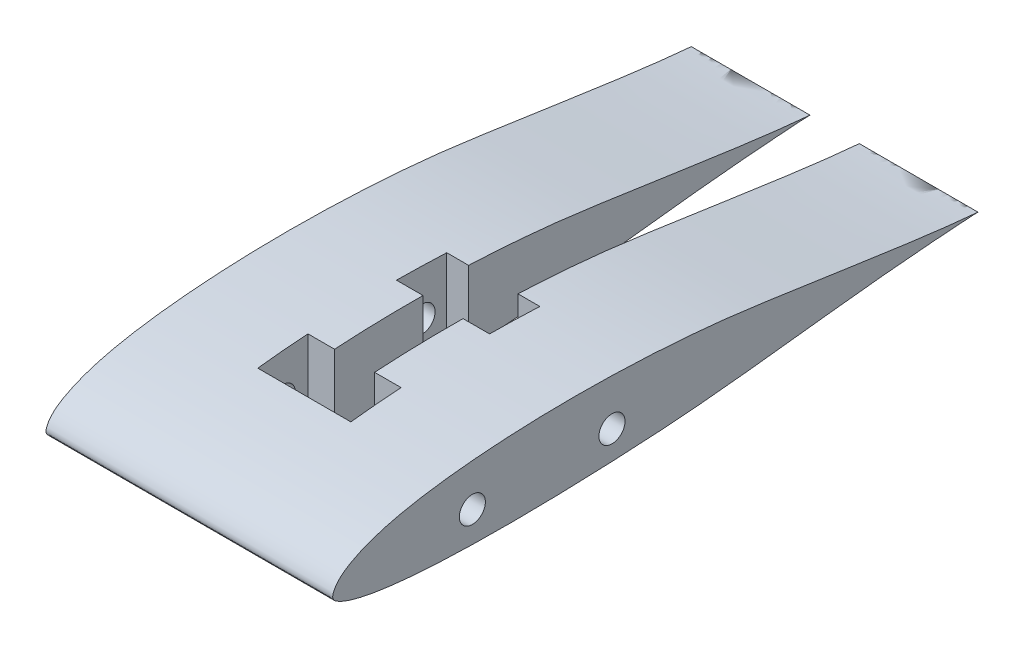
SolidWorks part; units mm, degrees
material "blue foam"
ref_plane "Front Plane" through (0, 0, 0) normal (0, 0, 1) x (1, 0, 0)
ref_plane "Top Plane" through (0, 0, 0) normal (0, 1, 0) x (1, 0, 0)
ref_plane "Right Plane" through (0, 0, 0) normal (1, 0, 0) x (0, 0, -1)
curve "Curve1"
  spline degree 3 poles (0, 0.9957, 0.0001) (0, 1.0011, -0.0001) (0, 0.9959, 0.0003) (0, 0.9917, 0.0009) (0, 0.9816, 0.0019) (0, 0.9692, 0.0034) (0, 0.953, 0.0054) (0, 0.9339, 0.008) (0, 0.9119, 0.0111) (0, 0.8872, 0.0148) (0, 0.8601, 0.019) (0, 0.8309, 0.0237) (0, 0.7998, 0.0287) (0, 0.7672, 0.0341) (0, 0.7332, 0.0396) (0, 0.6982, 0.0453) (0, 0.6625, 0.0509) (0, 0.6263, 0.0563) (0, 0.5898, 0.061) (0, 0.5529, 0.0649) (0, 0.5159, 0.0683) (0, 0.4788, 0.0709) (0, 0.4418, 0.0729) (0, 0.4052, 0.0743) (0, 0.3691, 0.0751) (0, 0.3338, 0.0752) (0, 0.2993, 0.0747) (0, 0.266, 0.0736) (0, 0.234, 0.072) (0, 0.2036, 0.0697) (0, 0.1748, 0.0669) (0, 0.1479, 0.0636) (0, 0.123, 0.0598) (0, 0.1002, 0.0554) (0, 0.0797, 0.0505) (0, 0.0614, 0.045) (0, 0.0455, 0.0391) (0, 0.0319, 0.0328) (0, 0.0207, 0.0264) (0, 0.0119, 0.0198) (0, 0.0055, 0.0129) (0, 0.0017, 0.0063) (0, -0.0006, 0) (0, 0.0012, -0.0062) (0, 0.0072, -0.0105) (0, 0.0154, -0.0148) (0, 0.0266, -0.019) (0, 0.0406, -0.0231) (0, 0.0572, -0.0268) (0, 0.0765, -0.0303) (0, 0.0982, -0.0334) (0, 0.1224, -0.0361) (0, 0.1489, -0.0384) (0, 0.1774, -0.0403) (0, 0.2079, -0.0418) (0, 0.2402, -0.0429) (0, 0.2741, -0.0436) (0, 0.3093, -0.0439) (0, 0.3458, -0.0438) (0, 0.3831, -0.0434) (0, 0.4212, -0.0425) (0, 0.4596, -0.0413) (0, 0.4983, -0.0398) (0, 0.537, -0.0377) (0, 0.5755, -0.035) (0, 0.6138, -0.0319) (0, 0.6516, -0.0285) (0, 0.6889, -0.0249) (0, 0.7253, -0.0212) (0, 0.7607, -0.0176) (0, 0.7946, -0.0144) (0, 0.8268, -0.0114) (0, 0.857, -0.0088) (0, 0.8849, -0.0066) (0, 0.9103, -0.0048) (0, 0.9328, -0.0033) (0, 0.9521, -0.0022) (0, 0.9685, -0.0014) (0, 0.9811, -0.0006) (0, 0.9914, -0.0002) (0, 0.9957, 0.0001) (0, 1.0011, -0.0001) (0, 0.9959, 0.0003) knots -0.008618 -0.003909 -0.000992 0 0.000971 0.003796 0.008389 0.014711 0.022678 0.032194 0.043158 0.055448 0.068945 0.083521 0.099035 0.115338 0.132292 0.149749 0.167548 0.185533 0.203607 0.221802 0.240095 0.258381 0.276594 0.294616 0.312363 0.329758 0.346689 0.363076 0.378824 0.393854 0.408071 0.421404 0.433793 0.445185 0.455538 0.464887 0.47323 0.480558 0.486907 0.492238 0.496718 0.500526 0.503606 0.506178 0.509479 0.514052 0.519911 0.527046 0.535435 0.545049 0.555862 0.56782 0.580876 0.59495 0.609978 0.62587 0.642537 0.659879 0.677794 0.696173 0.714893 0.733839 0.75289 0.771908 0.790875 0.809755 0.828448 0.846871 0.864891 0.882382 0.899178 0.915117 0.930053 0.943838 0.95634 0.967439 0.977019 0.98501 0.991382 0.996091 0.999008 1 1.000971 1.003796 1.008389 periodic
sketch "Sketch4" plane through (0, 0, 0) normal (1, 0, 0) x (0, 0, -1)
  circle A0 centre (75, 3) radius 7
  circle A1 centre (150, 3) radius 7
  spline S1 degree 3 poles (345.1151, 5.4929) (346.9717, 5.4701) (345.1672, 5.5769) (343.7104, 5.7505) (340.2081, 6.0536) (335.9082, 6.496) (330.2937, 7.1155) (323.6606, 7.8968) (316.0039, 8.8659) (307.4314, 10.0042) (298.0209, 11.3058) (287.8664, 12.7594) (277.0629, 14.3406) (265.7085, 16.0231) (253.9004, 17.7629) (241.7421, 19.5414) (229.3329, 21.2784) (216.7686, 22.9557) (204.0805, 24.3992) (191.2897, 25.5447) (178.4332, 26.4964) (165.5574, 27.2172) (152.7349, 27.7103) (140.033, 28.0006) (127.5202, 28.0603) (115.2651, 27.9176) (103.3345, 27.5564) (91.7997, 26.9993) (80.7245, 26.2418) (70.1757, 25.3057) (60.2167, 24.1813) (50.9051, 22.8883) (42.295, 21.4084) (34.4265, 19.7795) (27.3348, 17.958) (21.0458, 15.9433) (15.5469, 13.8243) (10.8693, 11.5795) (7.0245, 9.2761) (4.0072, 6.9442) (1.838, 4.5402) (0.5395, 2.2053) (-0.2175, 0.0328) (0.4427, -2.1339) (2.5539, -3.5745) (5.408, -5.0315) (9.3222, -6.4314) (14.1757, -7.7519) (19.9704, -8.9686) (26.6659, -10.0543) (34.2295, -11.0068) (42.6237, -11.8126) (51.8004, -12.4681) (61.7097, -12.9778) (72.2936, -13.3342) (83.4917, -13.5412) (95.2361, -13.5975) (107.4564, -13.5091) (120.0777, -13.2803) (133.0203, -12.9149) (146.2013, -12.421) (159.535, -11.7907) (172.9325, -11.0348) (186.3242, -10.1051) (199.6597, -8.9724) (212.9044, -7.6895) (226.0093, -6.2936) (238.9028, -4.8296) (251.5113, -3.3631) (263.7389, -1.9392) (275.4854, -0.6149) (286.6399, 0.5905) (297.0964, 1.6567) (306.7557, 2.5706) (315.5196, 3.3339) (323.3092, 3.9605) (330.0225, 4.4486) (335.6905, 4.8424) (340.0425, 5.1747) (343.624, 5.3804) (345.1151, 5.4929) (346.9717, 5.4701) (345.1672, 5.5769) knots -0.008618 -0.003909 -0.000992 0 0.000971 0.003796 0.008389 0.014711 0.022678 0.032194 0.043158 0.055448 0.068945 0.083521 0.099035 0.115338 0.132292 0.149749 0.167548 0.185533 0.203607 0.221802 0.240095 0.258381 0.276594 0.294616 0.312363 0.329758 0.346689 0.363076 0.378824 0.393854 0.408071 0.421404 0.433793 0.445185 0.455538 0.464887 0.47323 0.480558 0.486907 0.492238 0.496718 0.500526 0.503606 0.506178 0.509479 0.514052 0.519911 0.527046 0.535435 0.545049 0.555862 0.56782 0.580876 0.59495 0.609978 0.62587 0.642537 0.659879 0.677794 0.696173 0.714893 0.733839 0.75289 0.771908 0.790875 0.809755 0.828448 0.846871 0.864891 0.882382 0.899178 0.915117 0.930053 0.943838 0.95634 0.967439 0.977019 0.98501 0.991382 0.996091 0.999008 1 1.000971 1.003796 1.008389 only from (346.6, 5.4835) to (346.6, 5.4835)
  point P0 (0, 0)
  dimension "D5" = 14
  dimension "D6" = 14
  dimension "D1" = 346.6
  dimension "D3" = 75
  dimension "D4" = 150
  dimension "D7" = 3
extrude "Boss-Extrude1" add sketch "Sketch4" along normal mid plane 1864
sketch "Sketch5" plane through (0, 0, 0) normal (0, 1, 0) x (1, 0, 0)
  line L1 (77, 386.2835) -> (-77, 386.2835)
  line L2 (77, 386.2835) -> (77, -118.858)
  line L3 (77, -118.858) -> (-77, -118.858)
  line L4 (-77, 386.2835) -> (-77, -118.858)
  dimension "D1" = 77
  dimension "D2" = 77
extrude "Cut-Extrude1" cut sketch "Sketch5" against normal through all both and the other way through all flip side to cut
sketch "Sketch6" plane through (0, 0, 0) normal (0, 1, 0) x (1, 0, 0)
  line L0 (77, 346.6) -> (-77, 346.6) construction
  line L1 (-25, 61.75) -> (25, 61.75)
  line L2 (-25, 61.75) -> (-25, 88.75)
  line L3 (-25, 88.75) -> (25, 88.75)
  line L4 (25, 61.75) -> (25, 88.75)
  line L5 (25, 163.25) -> (-25, 163.25)
  line L6 (25, 163.25) -> (25, 136.25)
  line L7 (25, 136.25) -> (-25, 136.25)
  line L8 (-25, 163.25) -> (-25, 136.25)
  line L9 (-10.75, 136.25) -> (10.75, 136.25)
  line L10 (-10.75, 136.25) -> (-10.75, 88.75)
  line L11 (-10.75, 88.75) -> (10.75, 88.75)
  line L12 (10.75, 136.25) -> (10.75, 88.75)
  line L13 (13.25, 163.25) -> (-13.25, 163.25)
  line L14 (13.25, 163.25) -> (13.25, 346.6)
  line L15 (13.25, 346.6) -> (-13.25, 346.6)
  line L16 (-13.25, 163.25) -> (-13.25, 346.6)
  line L17 (13.25, 163.25) -> (13.25, 215) construction
  line L18 (-13.25, 215) -> (-13.25, 163.25) construction
  line L19 (25, 150) -> (25, 163.25) construction
  line L20 (-25, 163.25) -> (-25, 150) construction
  line L21 (10.75, 215) -> (10.75, 71.75) construction
  line L22 (-10.75, 71.75) -> (-10.75, 215) construction
  line L23 (25, 163.25) -> (13.25, 163.25) construction
  line L24 (25, 136.25) -> (9.6107, 136.25) construction
  line L25 (9.6107, 88.75) -> (25, 88.75) construction
  line L26 (0.75, 61.75) -> (25, 61.75) construction
extrude "Cut-Extrude2" cut sketch "Sketch6" against normal through all both and the other way through all contours L16 L5 L14 L15 | L5 L8 L7 L6 | L12 L7 L10 L3 | L1 L4 L3 L2
equation "\"D1@Sketch5\"=154/2"
equation "\"D2@Sketch5\"=154/2"
